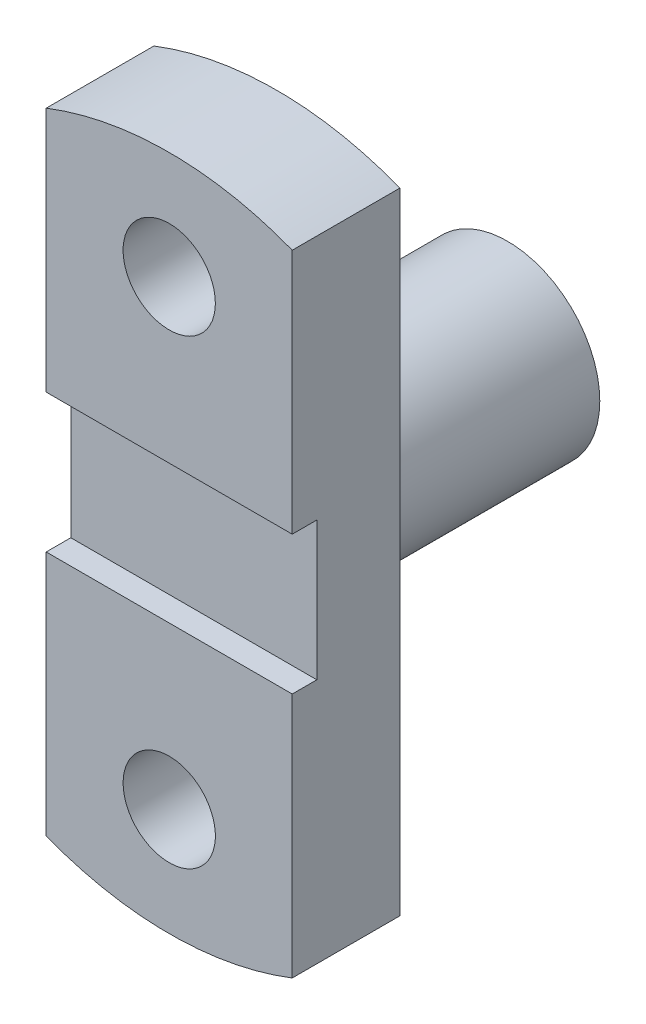
SolidWorks part; units mm, degrees
ref_plane "Front Plane" through (0, 0, 0) normal (0, 0, 1) x (1, 0, 0)
ref_plane "Top Plane" through (0, 0, 0) normal (0, 1, 0) x (1, 0, 0)
ref_plane "Right Plane" through (0, 0, 0) normal (1, 0, 0) x (0, 0, -1)
sketch "Sketch1" plane through (0, 0, 0) normal (0, 0, 1) x (1, 0, 0)
  line L0 (-40, 102.4695) -> (-40, -102.4695)
  line L2 (40, 102.4695) -> (40, -102.4695)
  line L3 (0, -55) -> (0, 55) construction
  line L4 (55, 0) -> (-55, 0) construction
  arc A0 (-40, -102.4695) -> (40, -102.4695) centre (0, 0) ccw
  arc A1 (40, 102.4695) -> (-40, 102.4695) centre (0, 0) ccw
  circle A2 centre (0, 75) radius 15
  circle A3 centre (0, -75) radius 15
  dimension "D1" = 110
  dimension "D3" = 75
  dimension "D4" = 30
  dimension "D2" = 80
extrude "Boss-Extrude1" add sketch "Sketch1" along normal blind 35
sketch "Sketch2" plane through (0, 0, 35) normal (0, 0, 1) x (1, 0, 0)
  line L0 (40, -102.4695) -> (40, 102.4695) construction
  line L1 (-40, -22.5) -> (40, -22.5)
  line L2 (-40, -22.5) -> (-40, 22.5)
  line L3 (-40, 22.5) -> (40, 22.5)
  line L4 (40, -22.5) -> (40, 22.5)
  line L5 (-40, -22.5) -> (40, 22.5) construction
  line L6 (-40, 22.5) -> (40, -22.5) construction
  point P0 (0, 0)
extrude "Cut-Extrude1" cut sketch "Sketch2" against normal blind 8
sketch "Sketch3" plane through (0, 0, 0) normal (0, 0, -1) x (-1, 0, 0)
  circle A0 centre (0, 0) radius 30
extrude "Boss-Extrude2" add sketch "Sketch3" along normal blind 75
